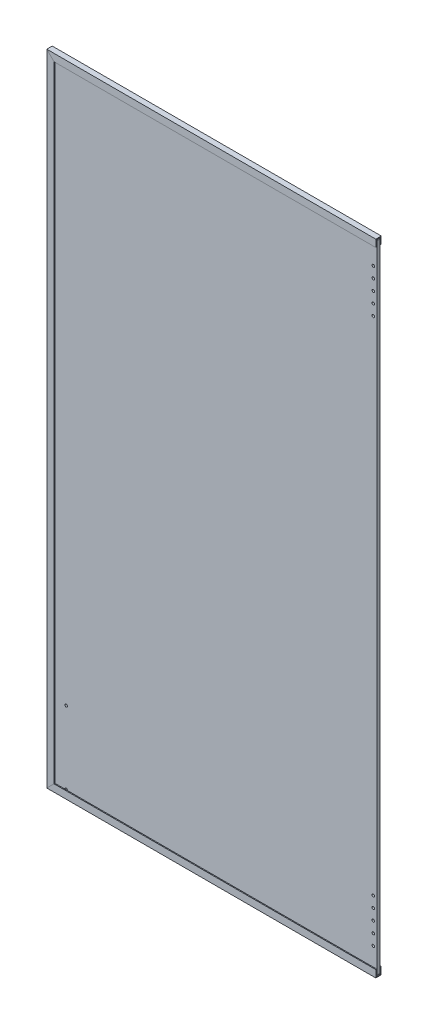
SolidWorks part; units mm, degrees
material "PC High Viscosity"
ref_plane "Front Plane" through (0, 0, 0) normal (0, 0, 1) x (1, 0, 0)
ref_plane "Top Plane" through (0, 0, 0) normal (0, 1, 0) x (1, 0, 0)
ref_plane "Right Plane" through (0, 0, 0) normal (1, 0, 0) x (0, 0, -1)
sketch "Shelf opening" plane through (0, 0, 0) normal (0, 0, 1) x (1, 0, 0)
  line L1 (0, 0) -> (577.85, 0)
  line L2 (0, 0) -> (0, 1092.2)
  line L3 (0, 1092.2) -> (577.85, 1092.2)
  line L4 (577.85, 0) -> (577.85, 1092.2)
  dimension "D1" = 577.85
  dimension "D2" = 1092.2
sketch "Sketch2" plane through (0, 0, 0) normal (0, 0, 1) x (1, 0, 0)
  line L0 (577.85, 0) -> (577.85, 1092.2) construction
  line L1 (3.175, 1104.9) -> (577.85, 1104.9)
  line L2 (3.175, 1104.9) -> (3.175, -12.7)
  line L3 (3.175, -12.7) -> (577.85, -12.7)
  line L4 (577.85, 1104.9) -> (577.85, -12.7)
  line L5 (0, 1092.2) -> (577.85, 1092.2) construction
  line L6 (0, 0) -> (0, 1092.2) construction
  line L7 (0, 0) -> (577.85, 0) construction
  dimension "D1" = 12.7
  dimension "D2" = 3.175
  dimension "D3" = 12.7
extrude "Frame outer dimensions" add sketch "Sketch2" along normal mid plane 9.525
sketch "Sketch3" plane through (0, 0, 4.7625) normal (0, 0, 1) x (1, 0, 0)
  line L0 (577.85, -12.7) -> (577.85, 1104.9) construction
  line L1 (577.85, 1092.2) -> (15.875, 1092.2)
  line L2 (577.85, 1092.2) -> (577.85, 0)
  line L3 (577.85, 0) -> (15.875, 0)
  line L4 (15.875, 1092.2) -> (15.875, 0)
  line L5 (577.85, 1104.9) -> (3.175, 1104.9) construction
  line L6 (3.175, 1104.9) -> (3.175, -12.7) construction
  line L7 (3.175, -12.7) -> (577.85, -12.7) construction
  dimension "D1" = 12.7
  dimension "D2" = 12.7
  dimension "D3" = 12.7
extrude "Frame inner dimensions" cut sketch "Sketch3" against normal through all
sketch "Sketch4" plane through (0, 0, 0) normal (0, 0, 1) x (1, 0, 0)
  line L0 (577.85, 1092.2) -> (577.85, 1104.9) construction
  line L1 (577.85, 1103.3125) -> (4.7625, 1103.3125)
  line L2 (577.85, 1103.3125) -> (577.85, -11.1125)
  line L3 (577.85, -11.1125) -> (4.7625, -11.1125)
  line L4 (4.7625, 1103.3125) -> (4.7625, -11.1125)
  line L5 (577.85, 1104.9) -> (3.175, 1104.9) construction
  line L6 (3.175, 1104.9) -> (3.175, -12.7) construction
  line L7 (3.175, -12.7) -> (577.85, -12.7) construction
  dimension "D1" = 1.5875
  dimension "D2" = 1.5875
  dimension "D3" = 1.5875
extrude "Frame profile" cut sketch "Sketch4" along normal offset from surface 1.5875 and the other way offset from surface (3.175 mm away) 1.5875 up to face at (293.6875, 546.1, 4.7625) other way up to face at (293.6875, 546.1, -4.7625)
sketch "Frame sections" plane through (0, 0, 4.7625) normal (0, 0, 1) x (1, 0, 0)
  line L0 (3.175, 1104.9) -> (15.875, 1092.2)
  line L1 (3.175, -12.7) -> (15.875, 0)
split "Frame section split" trim tools "Frame sections" bodies to split 103 resulting bodies 105 106 107
sketch "Sketch5" plane through (0, 0, 0) normal (0, 0, 1) x (1, 0, 0)
  line L0 (577.85, 1092.2) -> (577.85, 1104.9) construction
  line L1 (577.85, 1101.725) -> (6.35, 1101.725)
  line L2 (577.85, 1101.725) -> (577.85, -9.525)
  line L3 (577.85, -9.525) -> (6.35, -9.525)
  line L4 (6.35, 1101.725) -> (6.35, -9.525)
  line L5 (4.7625, 1103.3125) -> (577.85, 1103.3125) construction
  line L6 (4.7625, -11.1125) -> (4.7625, 1103.3125) construction
  line L7 (577.85, -11.1125) -> (4.7625, -11.1125) construction
  dimension "D1" = 1.5875
  dimension "D2" = 1.5875
  dimension "D3" = 1.5875
  dimension "D4" = 571.5
  dimension "D5" = 1111.25
extrude "Door panel" add sketch "Sketch5" along normal mid plane 5.588 separate body
sketch "Hinge positions" plane through (0, 0, 2.794) normal (0, 0, 1) x (1, 0, 0)
  line L0 (577.85, -9.525) -> (577.85, 1101.725) construction
  line L1 (577.85, 1069.975) -> (565.15, 1069.975)
  line L2 (577.85, 1069.975) -> (577.85, 974.725)
  line L3 (577.85, 974.725) -> (565.15, 974.725)
  line L4 (565.15, 1069.975) -> (565.15, 974.725)
  line L5 (565.15, 117.475) -> (577.85, 117.475)
  line L6 (565.15, 117.475) -> (565.15, 22.225)
  line L7 (565.15, 22.225) -> (577.85, 22.225)
  line L8 (577.85, 117.475) -> (577.85, 22.225)
  line L10 (0, 0) -> (577.85, 0) construction
  line L11 (0, 1092.2) -> (577.85, 1092.2) construction
  dimension "D1" = 95.25
  dimension "D2" = 12.7
  dimension "D3" = 22.225
  dimension "D4" = 22.225
  dimension "D5" = 952.5
sketch "Sketch8" plane through (0, 0, 2.794) normal (0, 0, 1) x (1, 0, 0)
  line L0 (565.15, 69.85) -> (577.85, 69.85) construction
  line L2 (565.15, 117.475) -> (565.15, 22.225) construction
  line L3 (577.85, 117.475) -> (577.85, 22.225) construction
  line L4 (565.15, 1022.35) -> (577.85, 1022.35) construction
  line L6 (565.15, 1069.975) -> (565.15, 974.725) construction
  line L7 (577.85, 1069.975) -> (577.85, 974.725) construction
  point P0 (571.5, 31.75)
  point P11 (571.5, 50.8)
  point P12 (571.5, 69.85)
  point P13 (571.5, 88.9)
  point P14 (571.5, 107.95)
  point P15 (571.5, 1003.3)
  point P16 (571.5, 1022.35)
  point P17 (571.5, 1041.4)
  point P18 (571.5, 1060.45)
  point P19 (571.5, 984.25)
  dimension "D3" = 19.05
  dimension "D1" = 5
  dimension "D2" = 2
hole_wizard "#8 Clearance Hole1" positions "Sketch8" profile "Sketch9" hole size "#8" standard "ANSI Inch" end condition through all
sketch "Sketch9" plane through (571.5, 31.75, 2.794) normal (1, 0, 0) x (0, -1, 0)
  line L0 (0, 0) -> (0, 7.5565)
  line L1 (0, 7.5565) -> (2.2479, 7.5565)
  line L2 (2.2479, 7.5565) -> (2.2479, 0)
  line L5 (2.2479, 0) -> (0, 0)
  line L11 (0, -6.35) -> (0, 107.95) construction
  dimension "Thru Hole Dia." = 4.4958
  dimension "Thru Hole Depth" = 7.5565
sketch "Handle position" plane through (0, 0, 2.794) normal (0, 0, 1) x (1, 0, 0)
  line L0 (6.35, 1101.725) -> (6.35, -9.525) construction
  line L1 (6.35, 139.7) -> (44.45, 139.7)
  line L2 (6.35, 139.7) -> (6.35, -9.525)
  line L3 (6.35, -9.525) -> (44.45, -9.525)
  line L4 (44.45, 139.7) -> (44.45, -9.525)
  line L5 (6.35, -9.525) -> (577.85, -9.525) construction
  dimension "D1" = 149.225
  dimension "D2" = 38.1
sketch "Sketch11" plane through (0, 0, 2.794) normal (0, 0, 1) x (1, 0, 0)
  line L0 (34.925, 127) -> (34.925, 0) construction
  line L2 (6.35, 139.7) -> (6.35, -9.525) construction
  line L3 (6.35, -9.525) -> (44.45, -9.525) construction
  point P0 (34.925, 0)
  point P2 (34.925, 127)
  dimension "D1" = 28.575
  dimension "D2" = 9.525
  dimension "D3" = 136.525
hole_wizard "#8 Clearance Hole2" positions "Sketch11" profile "Sketch12" hole size "#8" standard "ANSI Inch" end condition through all
sketch "Sketch12" plane through (34.925, 0, 2.794) normal (1, 0, 0) x (0, -1, 0)
  line L0 (0, 0) -> (0, 7.5565)
  line L1 (0, 7.5565) -> (2.2479, 7.5565)
  line L2 (2.2479, 7.5565) -> (2.2479, 0)
  line L5 (2.2479, 0) -> (0, 0)
  line L11 (0, -6.35) -> (0, 107.95) construction
  dimension "Thru Hole Dia." = 4.4958
  dimension "Thru Hole Depth" = 7.5565
mirror "Mirror1" about plane through (0, 0, 0) normal (1, 0, 0) of bodies 105 106 107 113 108
delete or keep bodies "Body-Delete/Keep 1" type keep bodies bodies 105 106 107 113
delete or keep bodies "Body-Delete/Keep 2" [suppressed] type keep bodies bodies 109 110 111 112
